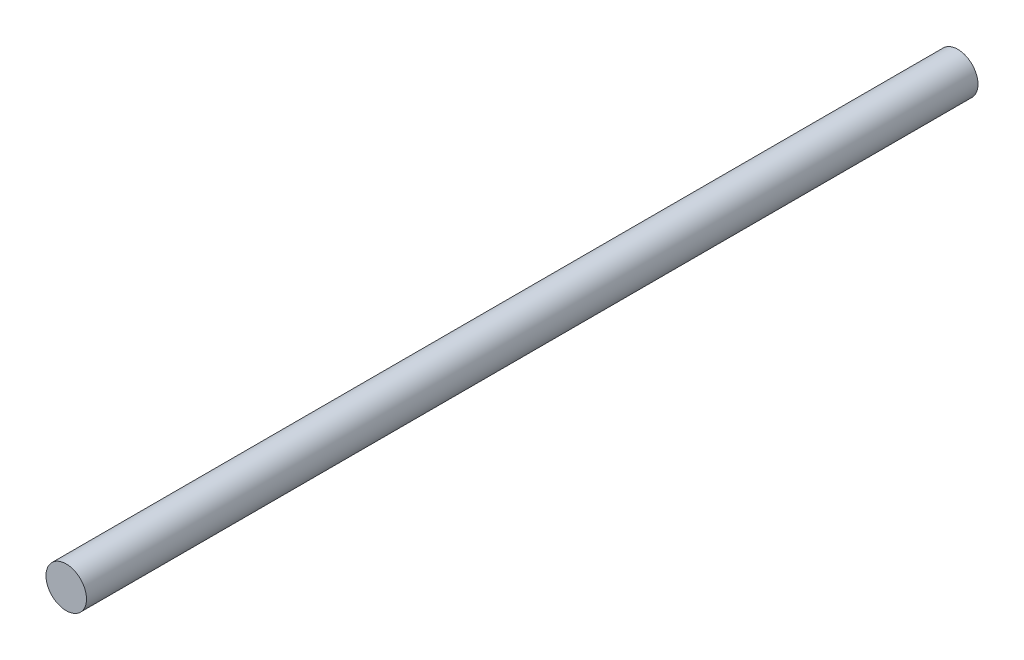
SolidWorks part; units mm, degrees
ref_plane "Front Plane" through (0, 0, 0) normal (0, 0, 1) x (1, 0, 0)
ref_plane "Top Plane" through (0, 0, 0) normal (0, 1, 0) x (1, 0, 0)
ref_plane "Right Plane" through (0, 0, 0) normal (1, 0, 0) x (0, 0, -1)
other "Configuration Table"
sketch "Sketch1" plane through (0, 0, 0) normal (0, 0, 1) x (1, 0, 0)
  circle A0 centre (744, 1550) radius 2.5
extrude "DET2_kablo_24V_motor_D5" add sketch "Sketch1" against normal blind 110 from offset 690 separate body
